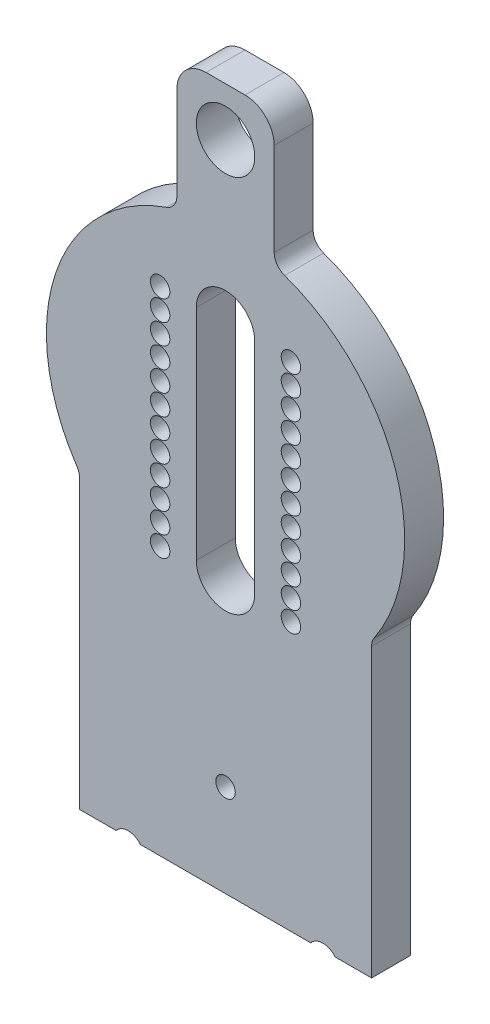
SolidWorks part; units mm, degrees
material "Aleación 1060"
ref_plane "Alzado" through (0, 0, 0) normal (0, 0, 1) x (1, 0, 0)
ref_plane "Planta" through (0, 0, 0) normal (0, 1, 0) x (1, 0, 0)
ref_plane "Vista lateral" through (0, 0, 0) normal (1, 0, 0) x (0, 0, -1)
sketch "Croquis1" plane through (0, 0, 0) normal (0, 0, 1) x (1, 0, 0)
  line L0 (-3, 0) -> (3, 0) construction
  line L1 (3, 0) -> (3, 10)
  line L2 (3, 0) -> (3, -12.5)
  line L3 (0, 0) -> (6.72, 0) construction
  line L4 (5.37, 0) -> (5.37, 10) construction
  line L5 (5.37, 0) -> (5.37, -12.5) construction
  line L6 (8.07, 10) -> (8.07, -12.5) construction
  line L7 (0, 0) -> (0, 18.4) construction
  line L8 (-8.07, 10) -> (-8.07, -12.5) construction
  line L9 (-5.37, 0) -> (-5.37, -12.5) construction
  line L10 (-5.37, 0) -> (-5.37, 10) construction
  line L11 (-3, 0) -> (-3, -12.5)
  line L12 (-3, 0) -> (-3, 10)
  line L13 (0, -18.4) -> (-15, -18.4) construction
  line L14 (-15, -10.6565) -> (-15, -40.6565)
  line L15 (15, -10.6565) -> (15, -40.6565)
  line L16 (-15, -40.6565) -> (15, -40.6565)
  arc A0 (15, -10.6565) -> (-15, -10.6565) centre (0, 0) ccw
  arc A1 (5.37, 10) -> (8.07, 10) centre (6.72, 10) cw construction
  arc A2 (5.37, -12.5) -> (8.07, -12.5) centre (6.72, -12.5) ccw construction
  arc A3 (-5.37, -12.5) -> (-8.07, -12.5) centre (-6.72, -12.5) cw construction
  arc A4 (-5.37, 10) -> (-8.07, 10) centre (-6.72, 10) ccw construction
  arc A5 (-3, 10) -> (3, 10) centre (0, 10) cw
  arc A6 (-3, -12.5) -> (3, -12.5) centre (0, -12.5) ccw
  circle A7 centre (-6.72, 10) radius 1
  circle A8 centre (6.72, 10) radius 1
  circle A9 centre (-6.72, 7.9) radius 1
  circle A10 centre (6.72, 7.9) radius 1
  circle A11 centre (-6.72, 5.8) radius 1
  circle A12 centre (6.72, 5.8) radius 1
  circle A13 centre (-6.72, 3.7) radius 1
  circle A14 centre (6.72, 3.7) radius 1
  circle A15 centre (-6.72, 1.6) radius 1
  circle A16 centre (6.72, 1.6) radius 1
  circle A17 centre (-6.72, -0.5) radius 1
  circle A18 centre (6.72, -0.5) radius 1
  circle A19 centre (-6.72, -2.6) radius 1
  circle A20 centre (6.72, -2.6) radius 1
  circle A21 centre (-6.72, -4.7) radius 1
  circle A22 centre (6.72, -4.7) radius 1
  circle A23 centre (-6.72, -6.8) radius 1
  circle A24 centre (6.72, -6.8) radius 1
  circle A25 centre (-6.72, -8.9) radius 1
  circle A26 centre (6.72, -8.9) radius 1
  circle A27 centre (-6.72, -11) radius 1
  circle A28 centre (6.72, -11) radius 1
  circle A29 centre (-6.72, -13.1) radius 1
  circle A30 centre (6.72, -13.1) radius 1
  dimension "D1" = 36.8
  dimension "D10" = 2
  dimension "D11" = 2
  dimension "D2" = 10
  dimension "D3" = 12.5
  dimension "D4" = 2.7
  dimension "D5" = 15
  dimension "D6" = 30
  dimension "D7" = 3
  dimension "D8" = 6.72
  dimension "D9" = 12.5
  dimension "D12" = 12
extrude "Saliente-Extruir1" add sketch "Croquis1" along normal blind 4
sketch "Croquis3" plane through (0, -40.6565, 0) normal (0, -1, 0) x (1, 0, 0)
  line L0 (-15, 4) -> (-15, 0) construction
  line L1 (0, 0) -> (0, 4) construction
  line L2 (-15, 0) -> (15, 0) construction
  line L3 (-15, 4) -> (15, 4) construction
  circle A0 centre (-10, 2) radius 1.25
  circle A1 centre (10, 2) radius 1.25
  dimension "D1" = 2.5
  dimension "D2" = 5
extrude "Cortar-Extruir1" cut sketch "Croquis3" against normal blind 4
sketch "Croquis4" plane through (0, 0, 4) normal (0, 0, 1) x (1, 0, 0)
  line L0 (0, 18.4) -> (0, 31.4) construction
  line L1 (5, 31.4) -> (-5, 31.4)
  line L2 (-5, 31.4) -> (-5, 17.7076)
  line L3 (5, 31.4) -> (5, 17.7076)
  line L4 (0, 29.4) -> (0, 31.4) construction
  arc A0 (15, -10.6565) -> (-15, -10.6565) centre (0, 0) ccw construction
  arc A5 (-5, 17.7076) -> (5, 17.7076) centre (0, 0) cw
  circle A6 centre (0, 26.4) radius 3
  dimension "D3" = 6
  dimension "D1" = 13
  dimension "D2" = 5
  dimension "D4" = 2
extrude "Saliente-Extruir2" add sketch "Croquis4" against normal up to vertex (4 mm away)
fillet "Redondeo1" radius 3 2 edges at (5, 31.4, 2) (-5, 31.4, 2)
fillet "Redondeo2" radius 1.6 4 edges at (15, -10.6565, 2) (5, 17.7076, 2) (-5, 17.7076, 2) (-15, -10.6565, 2)
sketch "Croquis5" plane through (0, 0, 4) normal (0, 0, 1) x (1, 0, 0)
  line L0 (-15, -11.1553) -> (-15, -40.6565) construction
  line L1 (-15, -40.6565) -> (15, -40.6565) construction
  line L2 (0, -40.6565) -> (0, -26.5541) construction
  circle A0 centre (-10, -41.6565) radius 1.6
  circle A1 centre (10, -41.6565) radius 1.6
  dimension "D1" = 5
  dimension "D3" = 3.2
  dimension "D2" = 1
extrude "Cortar-Extruir2" cut sketch "Croquis5" against normal up to vertex (4 mm away)
sketch "Croquis6" plane through (0, 0, 4) normal (0, 0, 1) x (1, 0, 0)
  line L0 (-8.751, -40.6565) -> (8.751, -40.6565) construction
  circle A0 centre (0, -31.1565) radius 1
  dimension "D1" = 2
  dimension "D2" = 9.5
extrude "Cortar-Extruir3" cut sketch "Croquis6" against normal up to vertex (4 mm away) up to point (15, -11.1553, 0)
